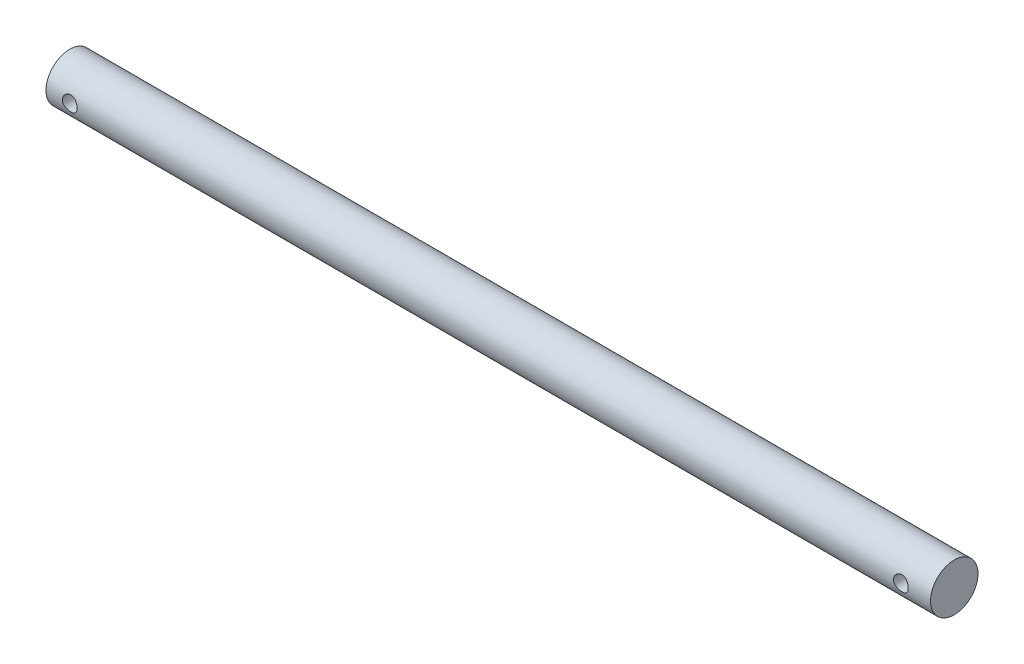
SolidWorks part; units mm, degrees
material "Plain Carbon Steel"
ref_plane "Front Plane" through (0, 0, 0) normal (0, 0, 1) x (1, 0, 0)
ref_plane "Top Plane" through (0, 0, 0) normal (0, 1, 0) x (1, 0, 0)
ref_plane "Right Plane" through (0, 0, 0) normal (1, 0, 0) x (0, 0, -1)
sketch "Sketch1" plane through (0, 0, 0) normal (1, 0, 0) x (0, 0, -1)
  circle A0 centre (0, 0) radius 4
  dimension "D1" = 8
extrude "Boss-Extrude1" add sketch "Sketch1" along normal mid plane 149
ref_plane "Plane1" through (0, 0, 4) normal (0, 0, 1) x (1, 0, 0)
hole_wizard "M3 Tapped Hole1" positions "Sketch3" profile "Sketch2" tap size "M3" standard "ISO" end condition through all
sketch "Sketch3" plane through (0, 0, 4) normal (0, 0, 1) x (1, 0, 0)
  line L0 (74.5, 0) -> (69.5, 0) construction
  line L1 (74.5, -4) -> (74.5, 4) construction
  line L3 (-70.5, 0) -> (-74.5, 0) construction
  line L4 (-74.5, 4) -> (-74.5, -4) construction
  point P0 (-70.5, 0)
  point P2 (69.5, 0)
  dimension "D1" = 5
  dimension "D2" = 4
sketch "Sketch2" plane through (-70.5, 0, 4) normal (1, 0, 0) x (0, -1, 0)
  line L0 (0, 0) -> (0, 8)
  line L1 (0, 8) -> (1.25, 8)
  line L2 (1.25, 8) -> (1.25, 0)
  line L5 (1.25, 0) -> (0, 0)
  line L11 (0, -6.35) -> (0, 107.95) construction
  dimension "Thru Tap Drill Dia." = 2.5
  dimension "Thru Tap Drill Depth" = 8
cosmetic thread "Hole Thread1"
cosmetic thread "Hole Thread2"
